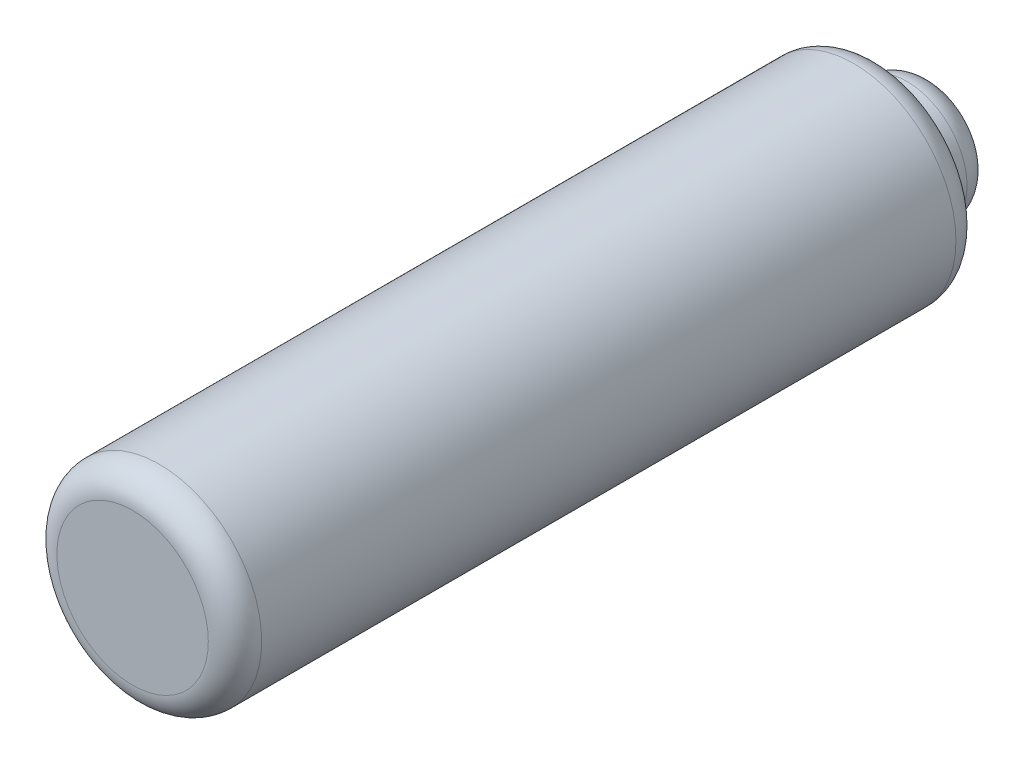
SolidWorks part; units mm, degrees
ref_plane "Front Plane" through (0, 0, 0) normal (0, 0, 1) x (1, 0, 0)
ref_plane "Top Plane" through (0, 0, 0) normal (0, 1, 0) x (1, 0, 0)
ref_plane "Right Plane" through (0, 0, 0) normal (1, 0, 0) x (0, 0, -1)
sketch "Sketch1" plane through (0, 0, 0) normal (0, 0, 1) x (1, 0, 0)
  circle A0 centre (0, 0) radius 3.835
  dimension "D1" = 7.67
extrude "Boss-Extrude1" add sketch "Sketch1" along normal mid plane 28
sketch "Sketch2" plane through (0, 0, -14) normal (0, 0, -1) x (-1, 0, 0)
  circle A0 centre (0, 0) radius 2.25
  dimension "D1" = 4.5
extrude "Boss-Extrude2" add sketch "Sketch2" along normal blind 2
fillet "Fillet1" radius 1 3 edges at (3.835, 0, 14) (3.835, 0, -14) (-2.25, 0, -16)
